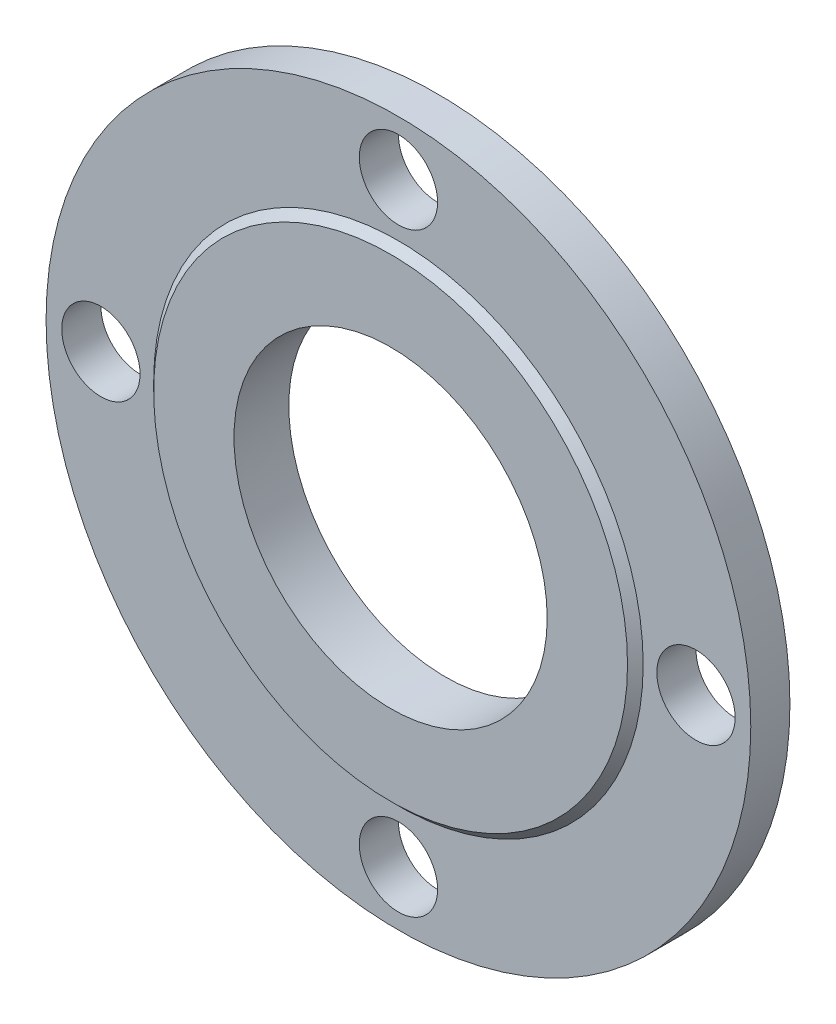
SolidWorks part; units mm, degrees
material "AISI 4340 Steel, annealed"
ref_plane "Front Plane" through (0, 0, 0) normal (0, 0, 1) x (1, 0, 0)
ref_plane "Top Plane" through (0, 0, 0) normal (0, 1, 0) x (1, 0, 0)
ref_plane "Right Plane" through (0, 0, 0) normal (1, 0, 0) x (0, 0, -1)
sketch "Sketch1" plane through (0, 0, 0) normal (0, 0, 1) x (1, 0, 0)
  circle A0 centre (0, 0) radius 12.7
  circle A1 centre (0, 0) radius 28.575
  dimension "OD" = 57.15
  dimension "ID" = 25.4
extrude "Boss-Extrude1" add sketch "Sketch1" along normal mid plane 3.175
sketch "Sketch8" plane through (0, 0, 0) normal (0, 0, 1) x (1, 0, 0)
  circle A0 centre (0, 0) radius 19.8501
  circle A1 centre (0, 0) radius 12.7
  circle A2 centre (0, 0) radius 12.7 construction
  dimension "seal element od" = 39.7002
extrude "Boss-Extrude2" add sketch "Sketch8" along normal mid plane 4.445 separate body
chamfer "Chamfer1" distance 0.635 angle 45 2 edges at (19.8501, 0, -2.2225) (19.8501, 0, 2.2225)
sketch "Sketch9" plane through (0, 0, 0) normal (0, 0, 1) x (1, 0, 0)
  circle A0 centre (0, 0) radius 19.8501
  circle A1 centre (0, 0) radius 19.8501 construction
extrude "Cut-Extrude1" cut sketch "Sketch9" against normal through all both and the other way through all
sketch "Sketch10" plane through (0, 0, 1.5875) normal (0, 0, 1) x (1, 0, 0)
  circle A0 centre (0, 0) radius 24.13 construction
  circle A1 centre (0, 24.13) radius 3.175
  circle A2 centre (24.13, 0) radius 3.175
  circle A3 centre (0, -24.13) radius 3.175
  circle A4 centre (-24.13, 0) radius 3.175
  dimension "D1" = 48.26
  dimension "D2" = 6.35
extrude "Cut-Extrude2" cut sketch "Sketch10" against normal through all
equation "\"D1@Chamfer1\"=(\"sealing element width@Boss-Extrude2\"-\"thick@Boss-Extrude1\")/2"
